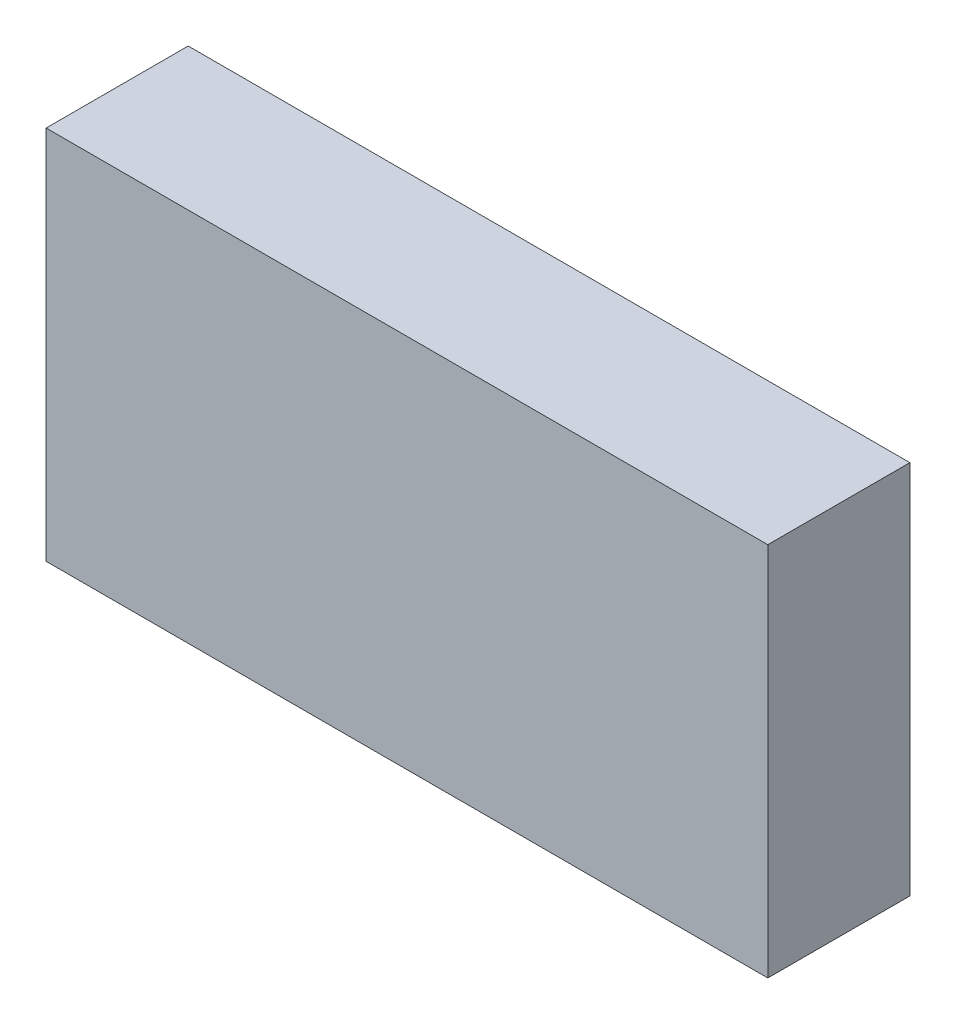
SolidWorks part; units mm, degrees
ref_plane "Front Plane" through (0, 0, 0) normal (0, 0, 1) x (1, 0, 0)
ref_plane "Top Plane" through (0, 0, 0) normal (0, 1, 0) x (1, 0, 0)
ref_plane "Right Plane" through (0, 0, 0) normal (1, 0, 0) x (0, 0, -1)
sketch "Sketch1" plane through (0, 0, 0) normal (0, 0, 1) x (1, 0, 0)
  line L0 (-1.27, 1.3716) -> (3.81, 1.3716)
  line L1 (3.81, 1.3716) -> (3.81, -1.27)
  line L2 (3.81, -1.27) -> (-1.27, -1.27)
  line L3 (-1.27, -1.27) -> (-1.27, 1.3716)
extrude "Component_Outline" add sketch "Sketch1" along normal blind 1 separate body
sketch3d "3DSketch1"
  line L0 (0, 0, 0) -> (1, 0, 0)
  line L1 (0, 0, 0) -> (0, 1, 0)
  line L2 (0, 0, 0) -> (0, 0, 1)
  point P0 (0, 0, 0)
